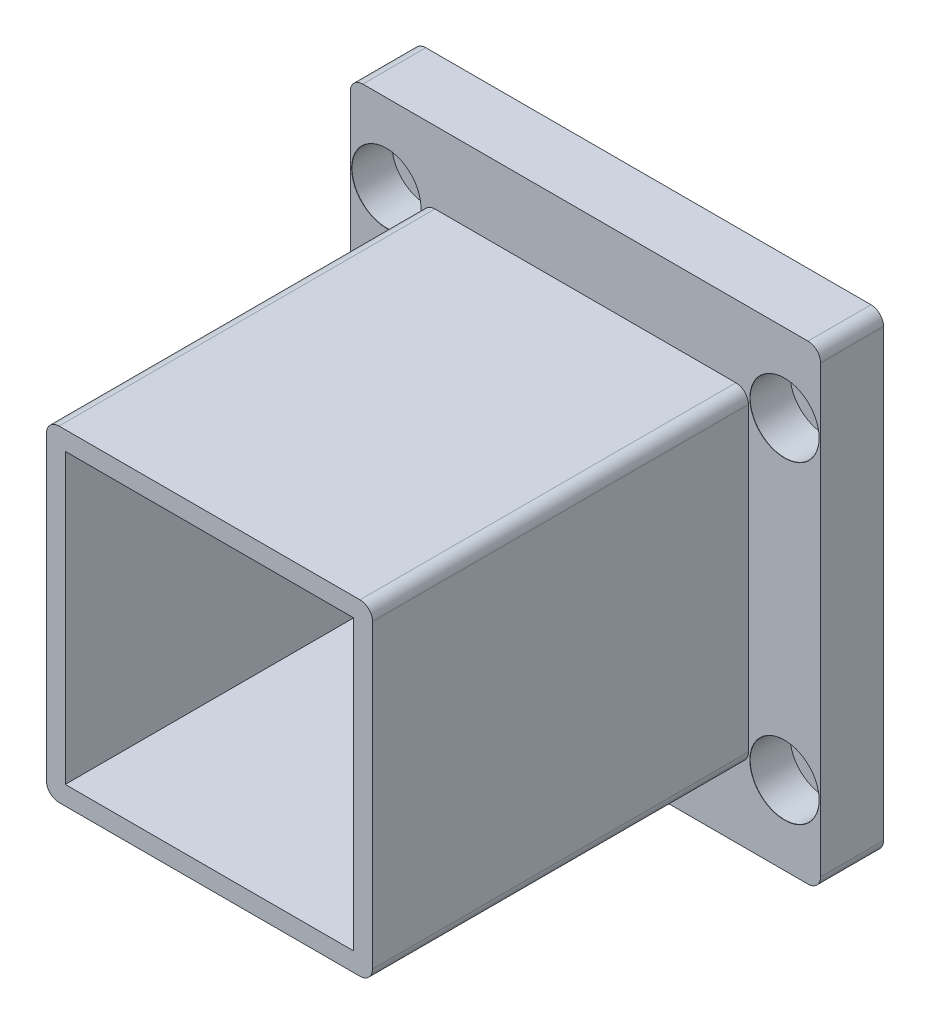
SolidWorks part; units mm, degrees
ref_plane "Front Plane" through (0, 0, 0) normal (1, 0, 0) x (0, 1, 0)
ref_plane "Top Plane" through (0, 0, 0) normal (0, 0, 1) x (0, 1, 0)
ref_plane "Right Plane" through (0, 0, 0) normal (0, 1, 0) x (-1, 0, 0)
sketch "Sketch1" plane through (0, 0, 0) normal (0, 0, 1) x (0, 1, 0)
  line L0 (-29.048, 30.1461) -> (-26.1566, 30.1461)
  line L1 (-29.048, 30.1461) -> (22.952, 30.1461)
  line L2 (-29.048, 30.1461) -> (-29.048, -21.8539)
  line L3 (-29.048, -21.8539) -> (22.952, -21.8539)
  line L4 (22.952, 30.1461) -> (22.952, -21.8539)
  line L6 (22.952, 30.1461) -> (15.3397, 30.1461)
  line L8 (-26.048, 27.1461) -> (-26.048, -18.8539)
  line L9 (-26.048, -18.8539) -> (19.952, -18.8539)
  line L10 (19.952, 27.1461) -> (19.952, -18.8539)
  line L11 (-26.048, 27.1461) -> (19.952, 27.1461)
  dimension "D1" = 46
  dimension "D2" = 46
  dimension "D3" = 3
extrude "Boss-Extrude1" add sketch "Sketch1" along normal blind 65 contours L4 L1 L0 L2 L3 L8 L11 L10 L9
sketch "Sketch3" plane through (0, 0, 0) normal (0, 0, -1) x (1, 0, 0)
  line L0 (-4.1461, 29.048) -> (-4.1461, -22.952)
  line L1 (-30.1461, 29.048) -> (21.8539, 29.048) construction
  line L2 (-30.1461, -22.952) -> (21.8539, -22.952) construction
  line L3 (21.8539, 29.048) -> (33.3539, 40.548)
  line L4 (-41.6461, 40.548) -> (33.3539, 40.548)
  line L5 (-41.6461, 40.548) -> (-41.6461, -34.452)
  line L6 (-41.6461, -34.452) -> (33.3539, -34.452)
  line L7 (33.3539, 40.548) -> (33.3539, -34.452)
  line L8 (-41.6461, 40.548) -> (33.3539, -34.452) construction
  line L9 (-41.6461, -34.452) -> (33.3539, 40.548) construction
  line L10 (27.6039, -21.952) -> (27.6039, 28.048)
  line L11 (27.6039, -28.702) -> (27.6039, 34.798)
  line L12 (-29.1461, 34.798) -> (20.8539, 34.798)
  line L13 (-35.8961, -21.952) -> (-35.8961, 28.048)
  line L14 (20.8539, -28.702) -> (-29.1461, -28.702)
  point P6 (-4.1461, 3.048)
  point P22 (27.6039, 3.048)
  line M5 (-30.1461, -22.952) -> (21.8539, -22.952)
  line M6 (21.8539, -22.952) -> (21.8539, 29.048)
  line M7 (21.8539, 29.048) -> (-30.1461, 29.048)
  line M8 (-30.1461, 29.048) -> (-30.1461, -22.952)
  line M9 (-27.1461, 26.048) -> (18.8539, 26.048)
  line M10 (18.8539, 26.048) -> (18.8539, -19.952)
  line M11 (18.8539, -19.952) -> (-27.1461, -19.952)
  line M12 (-27.1461, -19.952) -> (-27.1461, 26.048)
  dimension "D1" = 50
  dimension "D2" = 75
extrude "Boss-Extrude2" add sketch "Sketch3" along normal blind 5 contours L0 M9 M12 M11 | L0 M9 M11 M10 | L0 M7 M8 M5 M11 M12 M9 | L0 M7 M9 M10 M11 M5 M6 | L7 L4 L5 L6 M5 M8 M7 M6
sketch "Sketch8" plane through (0, 0, 0) normal (0, 0, 1) x (1, 0, 0)
  line L1 (-41.6461, 34.452) -> (33.3539, 34.452)
  line L2 (-41.6461, 34.452) -> (-41.6461, -40.548)
  line L3 (-41.6461, -40.548) -> (33.3539, -40.548)
  line L4 (33.3539, 34.452) -> (33.3539, -40.548)
  line L5 (-30.1461, 22.952) -> (21.8539, 22.952)
  line L6 (-30.1461, 22.952) -> (-30.1461, -29.048)
  line L7 (-30.1461, -29.048) -> (21.8539, -29.048)
  line L8 (21.8539, 22.952) -> (21.8539, -29.048)
extrude "Boss-Extrude3" add sketch "Sketch8" along normal blind 5.0471
fillet "Fillet1" radius 2 8 edges at (21.8539, -29.048, 35.0235) (-30.1461, -29.048, 35.0235) (-30.1461, 22.952, 35.0235) (21.8539, 22.952, 35.0235) (33.3539, 34.452, 0.0235) (-41.6461, 34.452, 0.0235) (-41.6461, -40.548, 0.0235) (33.3539, -40.548, 0.0235)
sketch "Sketch13" plane through (0, 0, 5.0471) normal (0, 0, 1) x (1, 0, 0)
  line L0 (-35.8961, 21.952) -> (-35.8961, -28.048)
  line L1 (-29.1461, -34.798) -> (20.8539, -34.798)
  line L2 (-41.6461, 34.452) -> (33.3539, -40.548)
  line L3 (27.6039, 21.952) -> (27.6039, -28.048)
  line L4 (-29.1461, 28.702) -> (20.8539, 28.702)
  point P0 (-35.8961, 21.952)
  point P1 (-35.8961, -28.048)
  point P12 (27.6039, 21.952)
  point P13 (27.6039, -28.048)
hole_wizard "CBORE for M6 Hex Socket Head Cap Screw2" positions "Sketch13" profile "Sketch15" counterbore size "M6" standard "ISO" end condition through all
sketch "Sketch15" plane through (-35.8961, 21.952, 5.0471) normal (1, 0, 0) x (0, -1, 0)
  line L0 (0, 0) -> (0, 10.0471)
  line L1 (0, 10.0471) -> (3.3, 10.0471)
  line L3 (3.3, 10.0471) -> (3.3, 6.4)
  line L4 (5.5, 6.4) -> (3.3, 6.4)
  line L5 (5.5, 6.4) -> (5.5, 0.025)
  line L6 (5.5, 0.025) -> (5.525, 0)
  line L7 (5.525, 0) -> (0, 0)
  line L8 (-5.5, 0.025) -> (-5.525, 0) construction
  line L11 (0, -6.35) -> (0, 107.95) construction
  dimension "Thru Hole Dia." = 6.6
  dimension "Thru Hole Depth" = 10.0471
  dimension "C'Bore Dia." = 11
  dimension "C'Bore Depth" = 6.4
  dimension "Near C'Sink Dia." = 11.05
  dimension "Near C'Sink Angle" = 90
